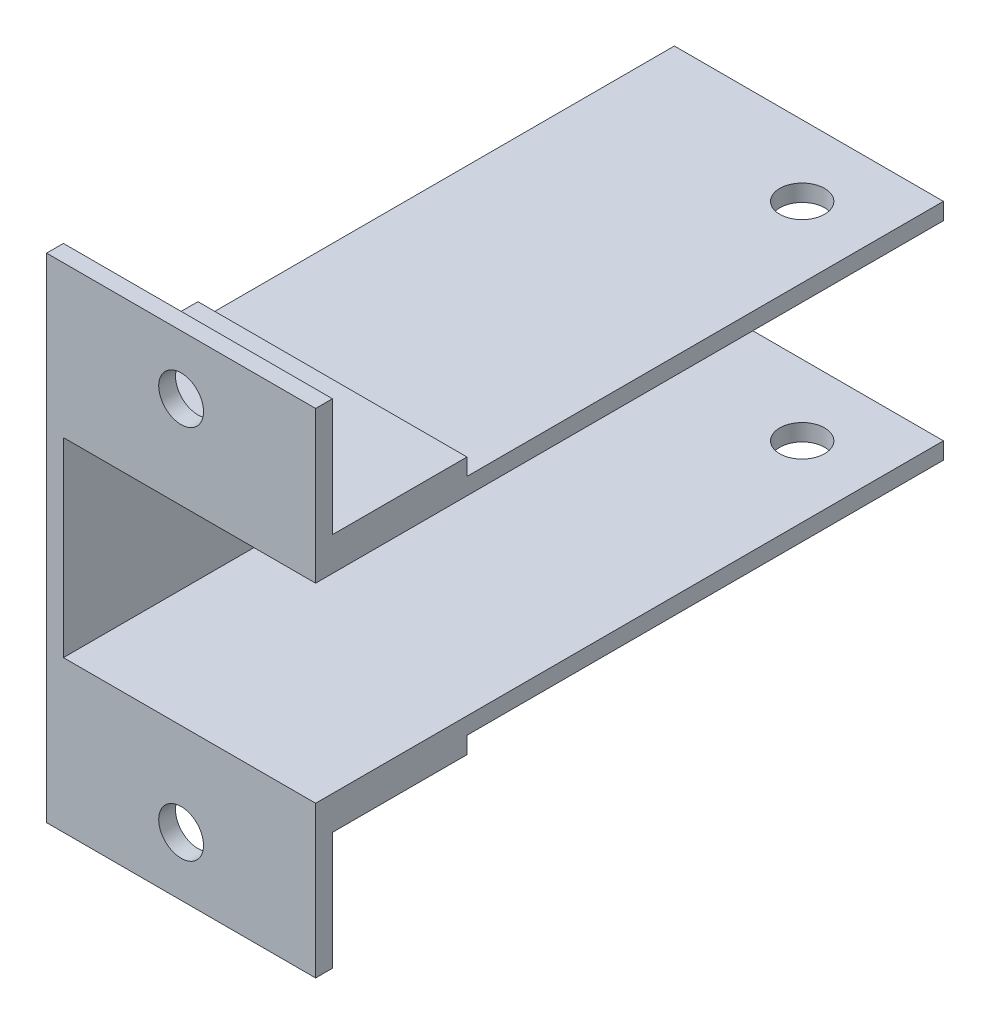
SolidWorks part; units mm, degrees
ref_plane "Alzado" through (0, 0, 0) normal (0, 0, 1) x (1, 0, 0)
ref_plane "Planta" through (0, 0, 0) normal (0, 1, 0) x (1, 0, 0)
ref_plane "Vista lateral" through (0, 0, 0) normal (1, 0, 0) x (0, 0, -1)
sketch "Croquis1" plane through (0, 0, 0) normal (0, 0, 1) x (1, 0, 0)
  line L0 (0, 31.75) -> (0, -31.75)
  line L5 (0, -31.75) -> (76.2, -31.75)
  line L6 (0, 31.75) -> (76.2, 31.75)
  line L7 (14.3493, 0) -> (-12.1213, 0) construction
  line L8 (4.7625, -26.9875) -> (76.2, -26.9875)
  line L9 (4.7625, 26.9875) -> (4.7625, -26.9875)
  line L10 (4.7625, 26.9875) -> (76.2, 26.9875)
  line L11 (76.2, -31.75) -> (76.2, -26.9875)
  line L12 (76.2, 31.75) -> (76.2, 26.9875)
  point P0 (0, 0)
  point P8 (0, 0)
  dimension "D1" = 63.5
  dimension "D2" = 76.2
  dimension "D3" = 4.7625
extrude "Saliente-Extruir1" add sketch "Croquis1" along normal mid plane 177.8
sketch "Croquis2" plane through (0, 0, 0) normal (1, 0, 0) x (0, 0, -1)
  line L0 (-88.9, 31.75) -> (88.9, 31.75) construction
  line L1 (-88.9, 69.85) -> (-84.1375, 69.85)
  line L2 (-88.9, 69.85) -> (-88.9, 31.75)
  line L3 (-88.9, 31.75) -> (-84.1375, 31.75)
  line L4 (-84.1375, 69.85) -> (-84.1375, 31.75)
  line L5 (-88.9, 26.9875) -> (-88.9, 31.75) construction
  line L6 (-46.0375, 31.75) -> (-84.1375, 31.75)
  line L7 (-46.0375, 31.75) -> (-46.0375, 36.5125)
  line L8 (-46.0375, 36.5125) -> (-84.1375, 36.5125)
  line L9 (-84.1375, 31.75) -> (-84.1375, 36.5125)
  point P9 (0, 0)
  dimension "D1" = 4.7625
  dimension "D2" = 38.1
  dimension "D3" = 4.7625
  dimension "D4" = 38.1
extrude "Saliente-Extruir2" add sketch "Croquis2" along normal through all contours L7 L8 L4 L6 | L4 L1 L2 L3
sketch "Croquis4" plane through (0, 0, 84.1375) normal (0, 0, -1) x (-1, 0, 0)
  line L0 (-38.1, 69.85) -> (-38.1, 36.5125) construction
  line L1 (0, 53.1812) -> (-76.2, 53.1812) construction
  line L4 (0, 36.5125) -> (0, 69.85)
  line L5 (0, 69.85) -> (-76.2, 69.85)
  line L6 (-76.2, 69.85) -> (-76.2, 36.5125)
  line L7 (-76.2, 36.5125) -> (0, 36.5125)
  line L8 (0, 36.5125) -> (0, 69.85)
  line L9 (0, 69.85) -> (-76.2, 69.85)
  line L10 (-76.2, 69.85) -> (-76.2, 36.5125)
  line L11 (-76.2, 36.5125) -> (0, 36.5125)
  circle A0 centre (-38.1, 53.1812) radius 6.35
  dimension "D2" = 12.7
  dimension "D1" = 0
extrude "Cortar-Extruir2" cut sketch "Croquis4" against normal blind 77.8 contours A0
mirror "Simetría3" about plane through (0, 0, 0) normal (0, 1, 0) of "Cortar-Extruir2", "Saliente-Extruir2"
sketch "Croquis5" plane through (0, -31.75, 0) normal (0, -1, 0) x (-1, 0, 0)
  line L0 (-56.2, 88.9) -> (-56.2, 11.8483) construction
  line L1 (0, 88.9) -> (-76.2, 88.9) construction
  line L2 (-81.7828, 68.9) -> (11.4691, 68.9) construction
  line L3 (-76.2, -46.0375) -> (-76.2, 88.9) construction
  circle A0 centre (-56.2, 68.9) radius 6.35
  point P8 (0, 0)
  point P9 (0, 0)
  dimension "D2" = 12.7
  dimension "D1" = 20
  dimension "D3" = 20
extrude "Cortar-Extruir3" cut sketch "Croquis5" against normal blind 77.8
